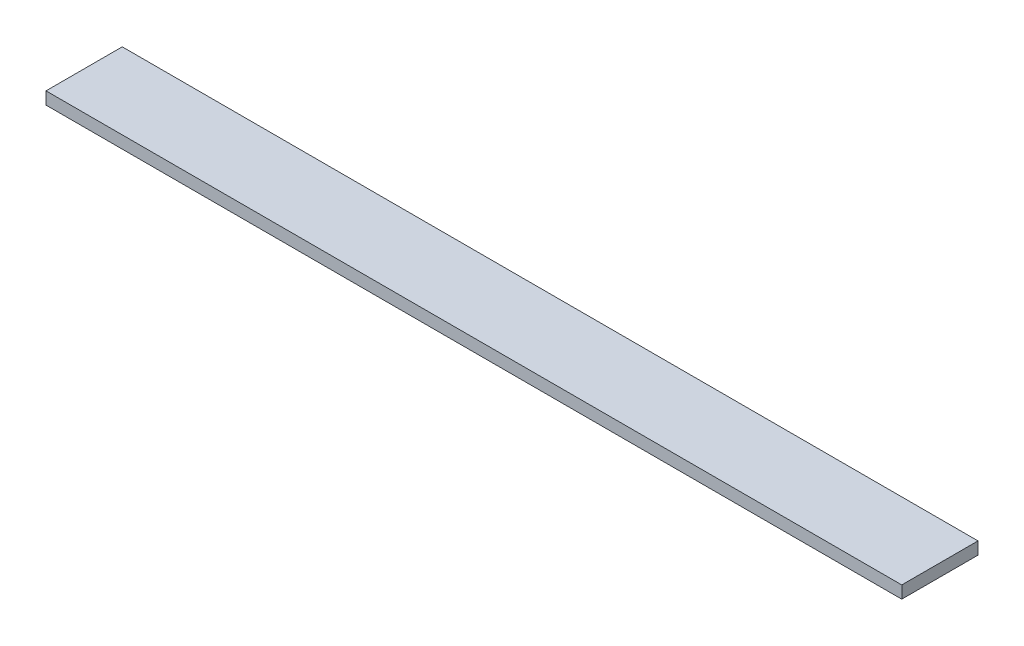
SolidWorks part; units mm, degrees
material "Pine"
ref_plane "Front Plane" through (0, 0, 0) normal (0, 0, 1) x (1, 0, 0)
ref_plane "Top Plane" through (0, 0, 0) normal (0, 1, 0) x (1, 0, 0)
ref_plane "Right Plane" through (0, 0, 0) normal (1, 0, 0) x (0, 0, -1)
sketch "Sketch1" plane through (0, 0, 0) normal (0, 1, 0) x (1, 0, 0)
  line L1 (-721.1739, 422.0587) -> (1915.6636, 422.0587)
  line L2 (-721.1739, 422.0587) -> (-721.1739, 187.1087)
  line L3 (-721.1739, 187.1087) -> (1915.6636, 187.1087)
  line L4 (1915.6636, 422.0587) -> (1915.6636, 187.1087)
  dimension "D1" = 234.95
  dimension "D2" = 2636.8375
extrude "Boss-Extrude1" add sketch "Sketch1" along normal blind 38.1 contours L1 L4 L3 L2
